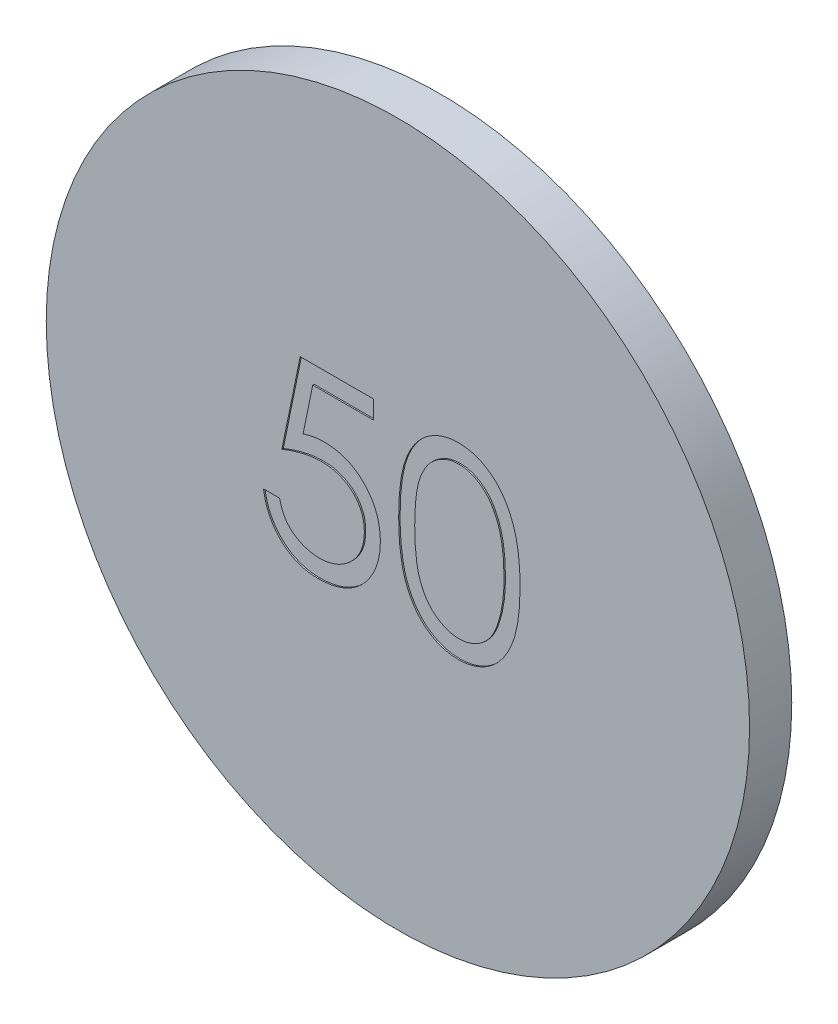
SolidWorks part; units mm, degrees
ref_plane "Front Plane" through (0, 0, 0) normal (1, 0, 0) x (0, 1, 0)
ref_plane "Top Plane" through (0, 0, 0) normal (0, 0, 1) x (0, 1, 0)
ref_plane "Right Plane" through (0, 0, 0) normal (0, 1, 0) x (-1, 0, 0)
sketch "Sketch1" plane through (0, 0, 0) normal (0, 0, 1) x (0, 1, 0)
  circle A0 centre (0, 0) radius 25
  dimension "D1" = 50
extrude "Boss-Extrude1" add sketch "Sketch1" along normal blind 3
sketch "Sketch3" plane through (0, 0, 3) normal (0, 0, 1) x (1, 0, 0)
  line L0 (-11.4811, 26.127) -> (-11.4811, -25.4536) construction
  line L1 (10.4239, 26.127) -> (10.4239, -25.4536) construction
  text T0 "10" font "Lato" height in points 48
extrude "Cut-Extrude1" [suppressed] cut sketch "Sketch3" against normal blind 0.1
sketch "Sketch5" plane through (0, 0, 3) normal (0, 0, 1) x (1, 0, 0)
  text T0 "20" font "Century Gothic" height in points 48
extrude "Cut-Extrude2" [suppressed] cut sketch "Sketch5" against normal blind 0.1
sketch "Sketch7" plane through (0, 0, 3) normal (0, 0, 1) x (1, 0, 0)
  text T0 "50" font "Century Gothic" height in points 48
extrude "Cut-Extrude3" cut sketch "Sketch7" against normal blind 0.1
